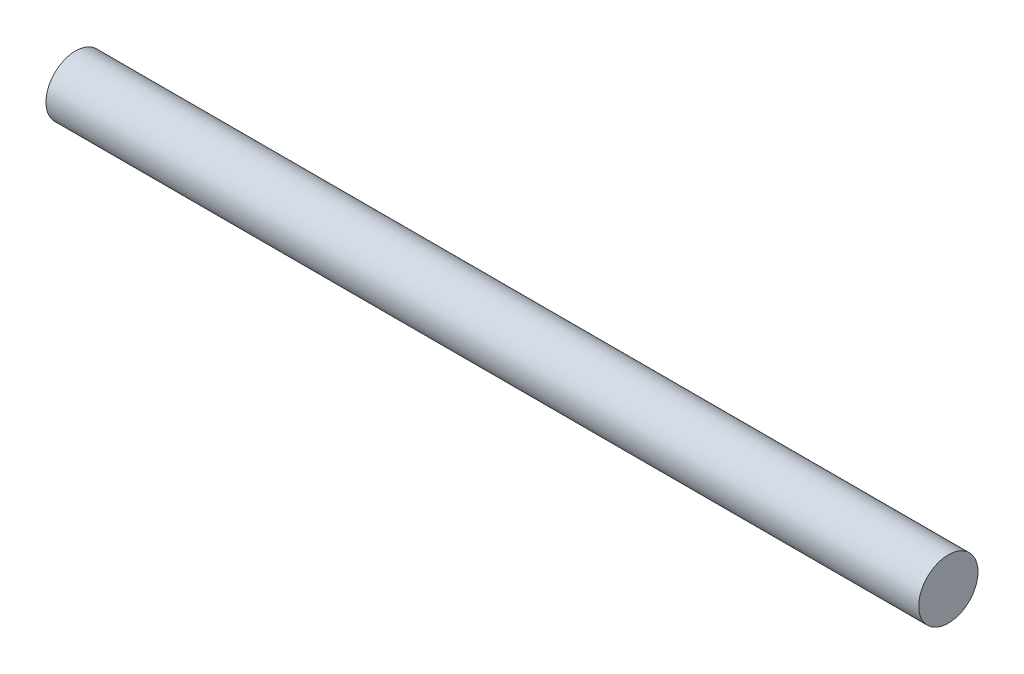
SolidWorks part; units mm, degrees
ref_plane "Front Plane" through (0, 0, 0) normal (0, 0, 1) x (1, 0, 0)
ref_plane "Top Plane" through (0, 0, 0) normal (0, 1, 0) x (1, 0, 0)
ref_plane "Right Plane" through (0, 0, 0) normal (1, 0, 0) x (0, 0, -1)
sketch "Sketch1" plane through (0, 0, 0) normal (1, 0, 0) x (0, 0, -1)
  circle A0 centre (0, 0) radius 1.25
  dimension "D1" = 2.5
extrude "Boss-Extrude1" add sketch "Sketch1" along normal blind 36.8 contours A0
